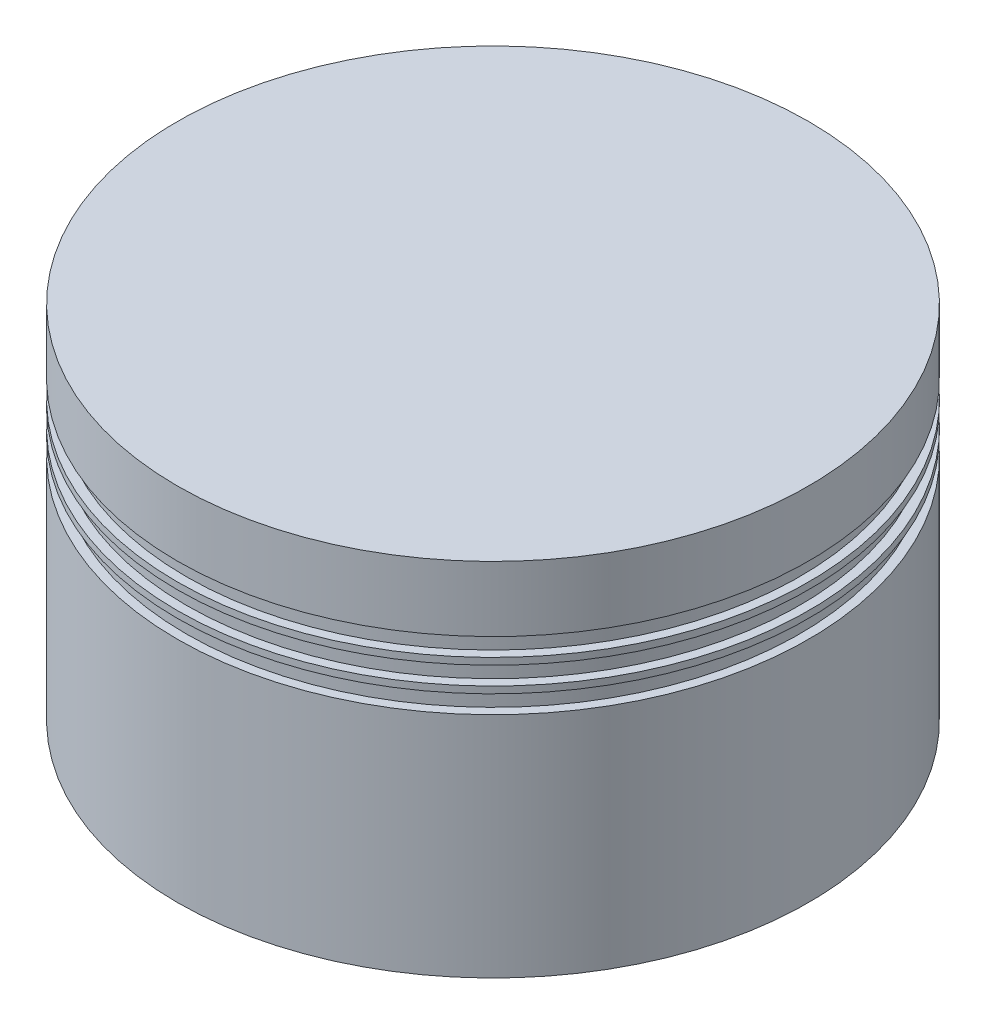
SolidWorks part; units mm, degrees
ref_plane "Front Plane" through (0, 0, 0) normal (0, 0, 1) x (1, 0, 0)
ref_plane "Top Plane" through (0, 0, 0) normal (0, 1, 0) x (1, 0, 0)
ref_plane "Right Plane" through (0, 0, 0) normal (1, 0, 0) x (0, 0, -1)
sketch "Sketch1" plane through (0, 0, 0) normal (0, 0, 1) x (1, 0, 0)
  line L0 (0, 0) -> (140, 0)
  line L1 (140, 0) -> (140, -28.8638)
  line L2 (0, -10) -> (130, -10)
  line L3 (130, -10) -> (130, -160)
  line L4 (0, 0) -> (0, -10)
  line L5 (140, -160) -> (130, -160)
  line L6 (140, -28.8638) -> (136, -28.8638)
  line L7 (136, -28.8638) -> (136, -36.8638)
  line L8 (136, -36.8638) -> (140, -36.8638)
  line L9 (140, -39.8638) -> (136, -39.8638)
  line L10 (136, -39.8638) -> (136, -47.8638)
  line L11 (136, -47.8638) -> (140, -47.8638)
  line L12 (140, -50.8638) -> (136, -50.8638)
  line L13 (136, -50.8638) -> (136, -58.8638)
  line L14 (136, -58.8638) -> (140, -58.8638)
  line L15 (140, -36.8638) -> (140, -39.8638)
  line L16 (140, -47.8638) -> (140, -50.8638)
  line L17 (140, 0) -> (140, -160) construction
  line L18 (140, -58.8638) -> (140, -160)
  line L19 (0, 0) -> (0, -96.3747) construction
  dimension "D1" = 140
  dimension "D2" = 160
  dimension "D4" = 4
  dimension "D5" = 8
  dimension "D6" = 28.8638
  dimension "D7" = 3
  dimension "D8" = 3
  dimension "D3" = 10
revolve "Revolve1" add sketch "Sketch1" angle 360 about L19
sketch "Sketch2" plane through (0, 0, 0) normal (0, 0, 1) x (1, 0, 0)
  line L0 (0, 0) -> (0, -140)
  line L1 (24, -150) -> (24, 0)
  line L2 (140, 0) -> (-140, 0) construction
  line L3 (24, 0) -> (0, 0)
  line L4 (24, -150) -> (10, -150)
  arc A1 (0, -140) -> (10, -150) centre (0, -150) cw
  dimension "D3" = 14
  dimension "D1" = 140
  dimension "D2" = 24
revolve "Revolve2" add sketch "Sketch2" angle 360 about L0
